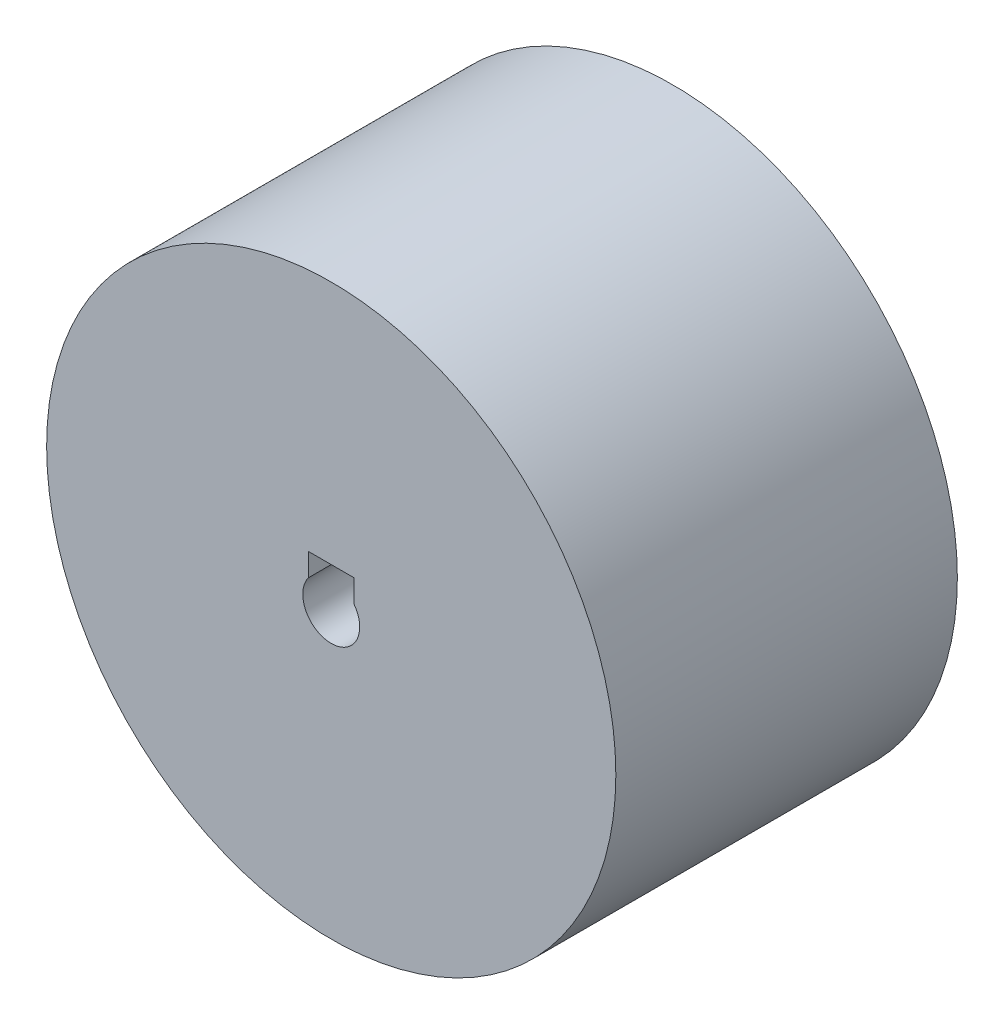
SolidWorks part; units mm, degrees
ref_plane "Plan de face" through (0, 0, 0) normal (0, 0, 1) x (1, 0, 0)
ref_plane "Plan de dessus" through (0, 0, 0) normal (0, 1, 0) x (1, 0, 0)
ref_plane "Plan de droite" through (0, 0, 0) normal (1, 0, 0) x (0, 0, -1)
sketch "Esquisse1" plane through (0, 0, 0) normal (0, 0, 1) x (1, 0, 0)
  circle A0 centre (0, 0) radius 25
  dimension "D1" = 50
extrude "Boss.-Extru.1" add sketch "Esquisse1" along normal blind 30
sketch "Esquisse14" plane through (0, 0, 0) normal (0, 0, -1) x (-1, 0, 0)
  circle A0 centre (0, 0) radius 2.5
  dimension "D1" = 5
extrude "Enlèv. mat.-Extru.1" cut sketch "Esquisse14" against normal through all
sketch "Esquisse15" plane through (0, 0, 0) normal (0, 0, -1) x (-1, 0, 0)
  line L0 (-2, 1.5) -> (-2, 3.5)
  line L1 (-2, 3.5) -> (2, 3.5)
  line L2 (2, 3.5) -> (2, 1.5)
  line L3 (2, 1.5) -> (-2, 1.5)
  circle A0 centre (0, 0) radius 2.5 construction
  dimension "D1" = 4
  dimension "D2" = 2
extrude "Enlèv. mat.-Extru.2" cut sketch "Esquisse15" against normal through all
